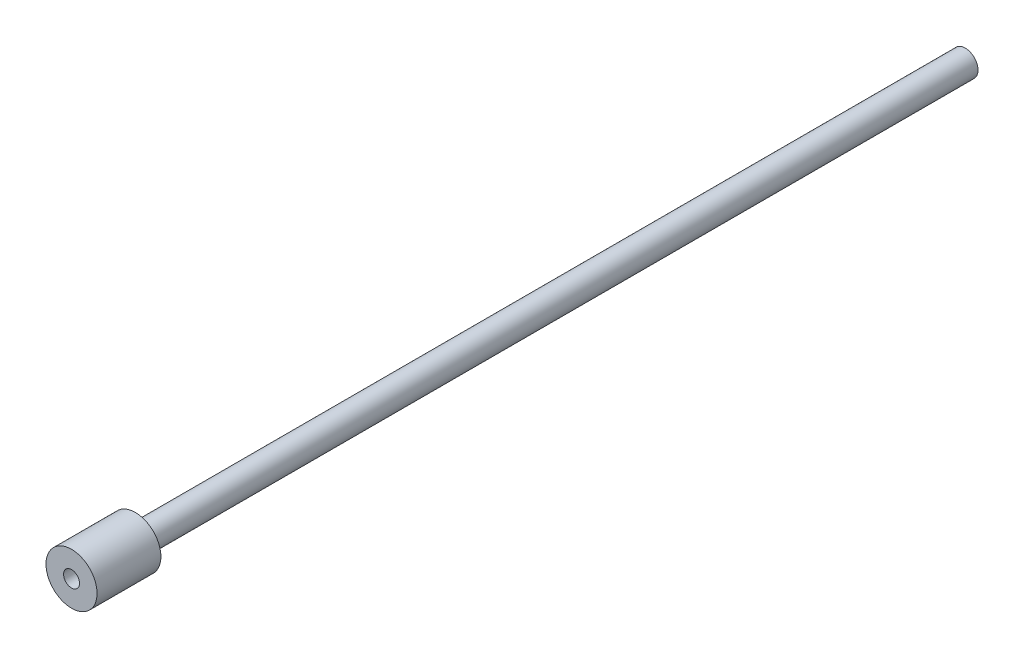
SolidWorks part; units mm, degrees
ref_plane "Front Plane" through (0, 0, 0) normal (0, 0, 1) x (1, 0, 0)
ref_plane "Top Plane" through (0, 0, 0) normal (0, 1, 0) x (1, 0, 0)
ref_plane "Right Plane" through (0, 0, 0) normal (1, 0, 0) x (0, 0, -1)
sketch "Sketch1" plane through (0, 0, 0) normal (0, 1, 0) x (1, 0, 0)
  line L0 (2.5, 0) -> (8, 0)
  line L1 (8, 0) -> (8, 20)
  line L2 (8, 20) -> (4, 20)
  line L3 (4, 20) -> (4, 279.9958)
  line L4 (4, 279.9958) -> (0, 279.9958)
  line L5 (0, 279.9958) -> (0, 10) construction
  line L6 (0, 10) -> (0, 279.9958)
  line L7 (0, 10) -> (2.5, 10)
  line L8 (2.5, 10) -> (2.5, 0)
  line L9 (0, 10) -> (0, 0) construction
  line L10 (0, 0) -> (0, 10) construction
  line L11 (0, 0) -> (2.5, 0) construction
  point P11 (8, 10)
  dimension "D1" = 16
  dimension "D2" = 20
  dimension "D3" = 270
  dimension "D4" = 8
  dimension "D5" = 5
revolve "Revolve1" add sketch "Sketch1" angle 360 about L5
